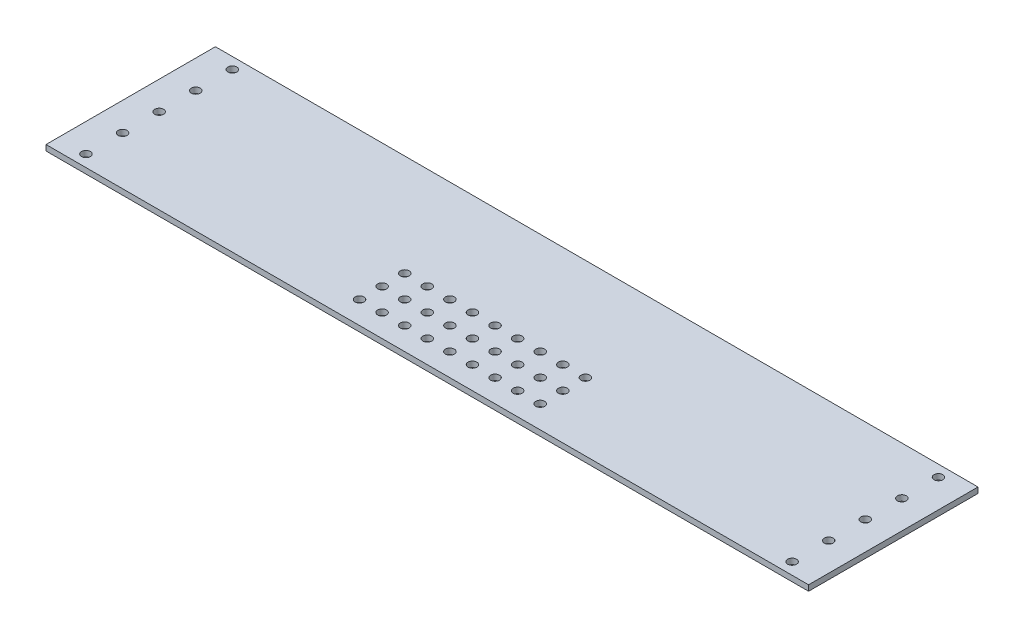
SolidWorks part; units mm, degrees
ref_plane "Front Plane" through (0, 0, 0) normal (0, 0, 1) x (1, 0, 0)
ref_plane "Top Plane" through (0, 0, 0) normal (0, 1, 0) x (1, 0, 0)
ref_plane "Right Plane" through (0, 0, 0) normal (1, 0, 0) x (0, 0, -1)
sketch "Sketch1" plane through (0, 0, 0) normal (0, 1, 0) x (1, 0, 0)
  line L0 (214.376, 95.25) -> (214.376, 0) construction
  line L1 (0, 0) -> (428.752, 0)
  line L2 (0, 0) -> (0, 95.25)
  line L3 (0, 95.25) -> (428.752, 95.25)
  line L4 (428.752, 0) -> (428.752, 95.25)
  line L5 (15.875, 88.9) -> (15.875, 68.326) construction
  circle A0 centre (15.875, 88.9) radius 2.4892
  circle A1 centre (412.877, 88.9) radius 2.4892
  circle A2 centre (15.875, 68.326) radius 2.4892
  circle A3 centre (15.875, 47.752) radius 2.4892
  circle A4 centre (15.875, 27.178) radius 2.4892
  circle A5 centre (15.875, 6.604) radius 2.4892
  circle A6 centre (412.877, 6.604) radius 2.4892
  circle A7 centre (412.877, 27.178) radius 2.4892
  circle A8 centre (412.877, 47.752) radius 2.4892
  circle A9 centre (412.877, 68.326) radius 2.4892
  dimension "D3" = 4.9784
  dimension "D4" = 15.875
  dimension "D5" = 6.35
  dimension "D1" = 95.25
  dimension "D2" = 428.752
  dimension "D6" = 214.376
  dimension "D8" = 20.574
  dimension "D7" = 5
extrude "Boss-Extrude1" add sketch "Sketch1" along normal blind 3.175
sketch "Sketch6" plane through (0, 0, 0) normal (0, -1, 0) x (-1, 0, 0)
  line L1 (0, 95.25) -> (0, 0) construction
  line L2 (0, 0) -> (-428.752, 0) construction
  line L3 (-214.376, 12.7) -> (-214.376, 25.4) construction
  line L4 (-214.376, 12.7) -> (-227.076, 12.7) construction
  line L5 (-214.376, 25.4) -> (-227.076, 25.4) construction
  line L6 (-214.376, 12.7) -> (-201.676, 12.7) construction
  circle A1 centre (-214.376, 12.7) radius 2.4892
  circle A2 centre (-214.376, 25.4) radius 2.4892
  circle A3 centre (-214.376, 38.1) radius 2.4892
  circle A4 centre (-227.076, 12.7) radius 2.4892
  circle A5 centre (-239.776, 12.7) radius 2.4892
  circle A6 centre (-252.476, 12.7) radius 2.4892
  circle A7 centre (-227.076, 25.4) radius 2.4892
  circle A8 centre (-227.076, 38.1) radius 2.4892
  circle A9 centre (-239.776, 25.4) radius 2.4892
  circle A10 centre (-239.776, 38.1) radius 2.4892
  circle A11 centre (-252.476, 25.4) radius 2.4892
  circle A12 centre (-252.476, 38.1) radius 2.4892
  circle A13 centre (-201.676, 12.7) radius 2.4892
  circle A14 centre (-201.676, 25.4) radius 2.4892
  circle A15 centre (-201.676, 38.1) radius 2.4892
  circle A16 centre (-188.976, 12.7) radius 2.4892
  circle A17 centre (-188.976, 25.4) radius 2.4892
  circle A18 centre (-188.976, 38.1) radius 2.4892
  circle A19 centre (-176.276, 12.7) radius 2.4892
  circle A20 centre (-176.276, 25.4) radius 2.4892
  circle A21 centre (-176.276, 38.1) radius 2.4892
  circle A22 centre (-163.576, 12.7) radius 2.4892
  circle A23 centre (-163.576, 25.4) radius 2.4892
  circle A24 centre (-163.576, 38.1) radius 2.4892
  circle A25 centre (-265.176, 25.4) radius 2.4892
  circle A26 centre (-265.176, 38.1) radius 2.4892
  circle A27 centre (-265.176, 12.7) radius 2.4892
  dimension "D1" = 4.9784
  dimension "D2" = 214.376
  dimension "D3" = 12.7
  dimension "D5" = 12.7
  dimension "D7" = 12.7
  dimension "D9" = 12.7
  dimension "D11" = 12.7
  dimension "D4" = 3
  dimension "D6" = 5
  dimension "D8" = 5
  dimension "D10" = 5
extrude "Cut-Extrude1" cut sketch "Sketch6" against normal blind 3.175
